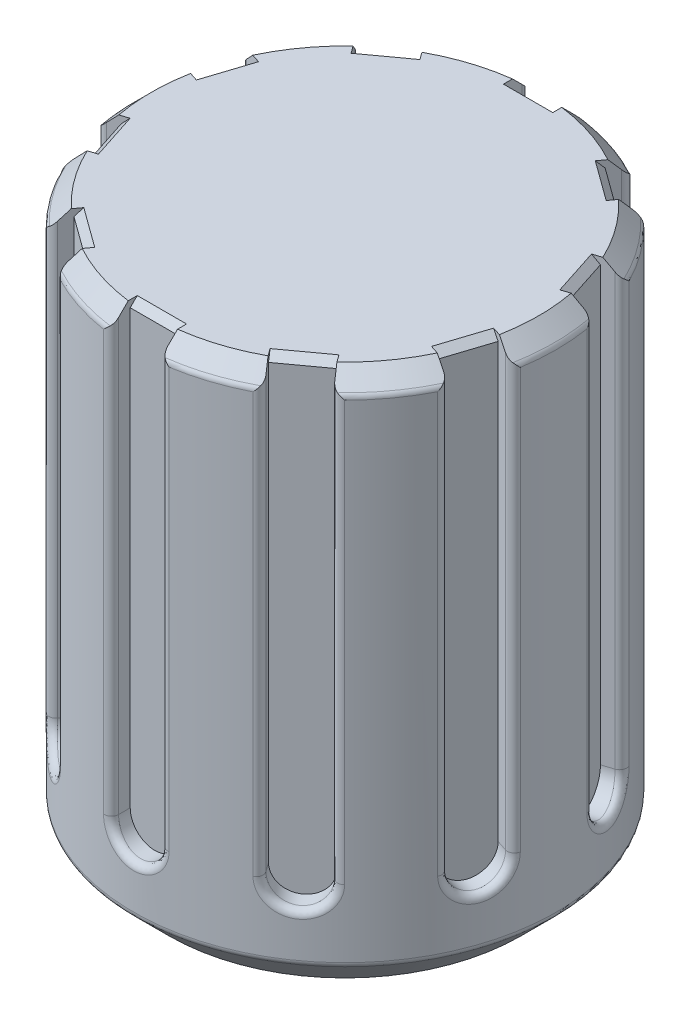
SolidWorks part; units mm, degrees
ref_plane "前视基准面" through (0, 0, 0) normal (0, 0, 1) x (1, 0, 0)
ref_plane "上视基准面" through (0, 0, 0) normal (0, 1, 0) x (1, 0, 0)
ref_plane "右视基准面" through (0, 0, 0) normal (1, 0, 0) x (0, 0, -1)
sketch "草图1" plane through (0, 0, 0) normal (0, 1, 0) x (1, 0, 0)
  circle A0 centre (0, 0) radius 6
  dimension "D1" = 12
extrude "凸台-拉伸1" add sketch "草图1" along normal blind 16
sketch "草图2" plane through (0, 0, 0) normal (0, -1, 0) x (1, 0, 0)
  circle A0 centre (0, 0) radius 3.75
  dimension "D1" = 7.5
extrude "切除-拉伸1" cut sketch "草图2" against normal blind 4.5
sketch "草图4" plane through (0, 0, 0) normal (0, -1, 0) x (1, 0, 0)
  circle A0 centre (0, 0) radius 3.1
  dimension "D1" = 6.2
extrude "切除-拉伸2" cut sketch "草图4" against normal blind 13.5
sketch "草图5" plane through (0, 16, 0) normal (0, 1, 0) x (1, 0, 0)
  circle A0 centre (0, 0) radius 13.5
  dimension "D1" = 27
extrude "切除-拉伸3" cut sketch "草图5" against normal blind 0.5
chamfer "倒角1" distance 0.5 angle 45 1 edges at (0, 15.5, 6)
sketch "草图6" plane through (0, 0, 0) normal (0, 0, 1) x (1, 0, 0)
  line L0 (0, 43) -> (0, 3) construction
  line L1 (0.7, 43) -> (0.7, 3)
  line L2 (-0.7, 43) -> (-0.7, 3)
  arc A0 (0.7, 43) -> (-0.7, 43) centre (0, 43) ccw
  arc A1 (-0.7, 3) -> (0.7, 3) centre (0, 3) ccw
  point P2 (0, 23)
  dimension "D1" = 1.4
  dimension "D2" = 40
  dimension "D3" = 3
extrude "切除-拉伸4" cut sketch "草图6" against normal blind 4 from offset 5.4 offset against normal yes
pattern_circular "阵列(圆周)1" count 10 every 36 about axis through (0, 0, 0) along (0, 1, 0) of "切除-拉伸4"
chamfer "倒角2" distance 0.2 angle 45 10 edges at (5.1357, 15.5, 1.6687) (3.174, 15.5, 4.3687) (0, 15.5, 5.4) (-3.174, 15.5, 4.3687) (-5.1357, 15.5, 1.6687) (-5.1357, 15.5, -1.6687) (-3.174, 15.5, -4.3687) (5.1357, 15.5, -1.6687) (3.174, 15.5, -4.3687) (0, 15.5, -5.4)
chamfer "倒角3" distance 0.4 angle 45 1 edges at (0, 0, -3.75)
chamfer "倒角4" distance 1 angle 45 1 edges at (0, 0, 6)
fillet "圆角4" radius 0.2 41 edges at (0.0788, 2.3044, -5.9995) (-0.7, 9, -5.959) (0.7, 9, -5.959) (-3.5267, 2.3, -4.8541) (-4.0689, 9, -4.4095) (-2.9363, 9, -5.2324) (3.6514, 3.6825, -4.761) (2.9363, 9, -5.2324) (4.0689, 9, -4.4095) (5.7064, 2.3, -1.8541) (5.4511, 9, -2.5072) (5.8837, 9, -1.1757) (5.6564, 3.6825, 2.0014) (5.8837, 9, 1.1757) (5.4511, 9, 2.5072) (3.3997, 3.6825, 4.9439) (4.0689, 9, 4.4095) (2.9363, 9, 5.2324) (-0.1556, 3.6825, 5.998) (0.7, 9, 5.959) (-0.7, 9, 5.959) (-3.6514, 3.6825, 4.761) (-2.9363, 9, 5.2324) (-4.0689, 9, 4.4095) (-5.7525, 3.6825, 1.7055) (-5.4511, 9, 2.5072) (-5.8837, 9, 1.1757) (-5.6564, 3.6825, -2.0014) (-5.8837, 9, -1.1757) (-5.4511, 9, -2.5072) (-6, 15, 0) (-4.8541, 15, 3.5267) (-1.8541, 15, 5.7063) (1.8541, 15, 5.7063) (4.8541, 15, 3.5267) (6, 15, 0) (4.8541, 15, -3.5267) (-4.8541, 15, -3.5267) (-1.8541, 15, -5.7063) (1.8541, 15, -5.7063) (0, 1, 6)
